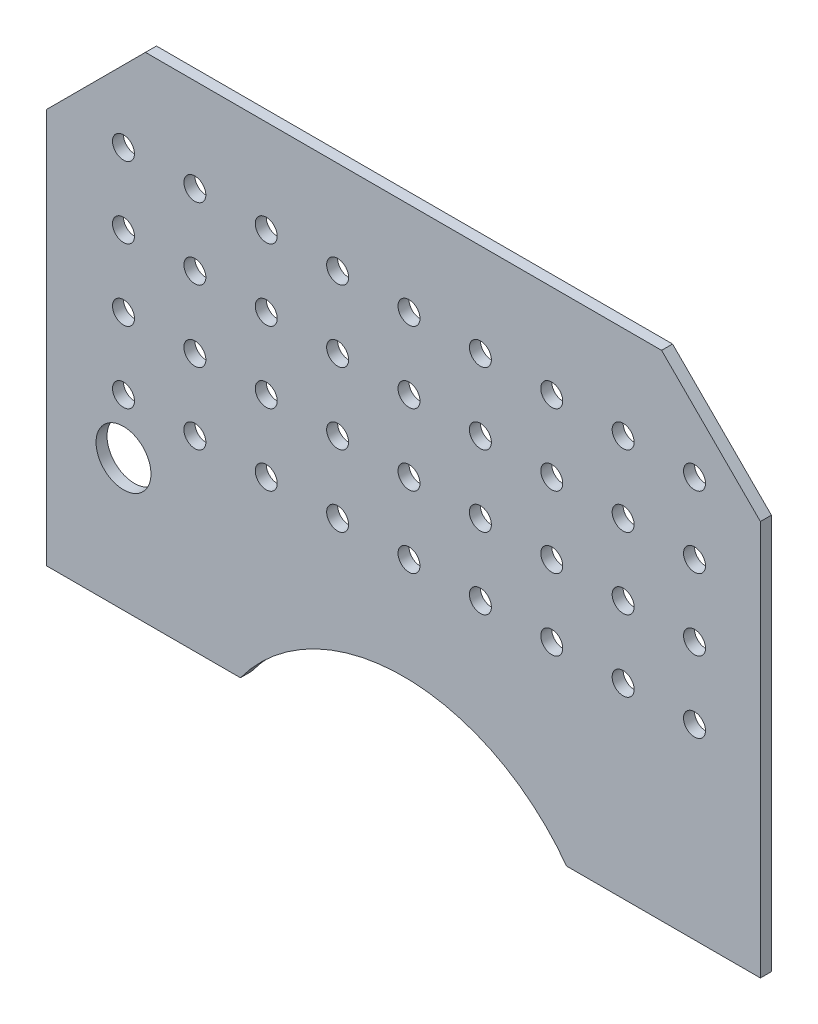
SolidWorks part; units mm, degrees
ref_plane "Front Plane" through (0, 0, 0) normal (0, 0, 1) x (1, 0, 0)
ref_plane "Top Plane" through (0, 0, 0) normal (0, 1, 0) x (1, 0, 0)
ref_plane "Right Plane" through (0, 0, 0) normal (1, 0, 0) x (0, 0, -1)
sketch "Эскиз1" plane through (0, 0, 0) normal (0, 0, 1) x (1, 0, 0)
  line L0 (3.78, -22.45) -> (2.015, -22.45)
  line L1 (0.76, -22.45) -> (3.78, -22.45) construction
  line L2 (2.015, -22.45) -> (2.015, -18.85)
  line L3 (2.015, -18.85) -> (2.915, -17.95)
  line L4 (2.915, -17.95) -> (7.615, -17.95)
  line L5 (5.265, -17.95) -> (5.265, -21.6965) construction
  line L6 (8.515, -18.85) -> (7.615, -17.95)
  line L7 (8.515, -22.45) -> (8.515, -18.85)
  line L8 (6.75, -22.45) -> (8.515, -22.45)
  arc A0 (6.75, -22.45) -> (3.78, -22.45) centre (5.265, -23.5365) ccw construction
  arc A1 (6.75, -22.45) -> (3.78, -22.45) centre (5.265, -23.5365) ccw
  dimension "D1" = 4.5
  dimension "D2" = 6.5
  dimension "D3" = 45
  dimension "D4" = 4.7
extrude "Бобышка-Вытянуть1" add sketch "Эскиз1" along normal blind 0.1
sketch "Эскиз2" plane through (0, 0, 0.1) normal (0, 0, 1) x (1, 0, 0)
  line L0 (2.015, -22.45) -> (3.78, -22.45) construction
  line L1 (2.015, -18.85) -> (2.015, -22.45) construction
  circle A0 centre (2.715, -21.25) radius 0.25
  dimension "D1" = 0.5
  dimension "D2" = 1.2
  dimension "D3" = 0.7
extrude "Вырез-Вытянуть1" cut sketch "Эскиз2" against normal through all
sketch "Эскиз3" plane through (0, 0, 0.1) normal (0, 0, 1) x (1, 0, 0)
  line L0 (2.015, -18.85) -> (2.015, -22.45) construction
  circle A0 centre (2.715, -20.75) radius 0.1
  circle A1 centre (2.715, -21.25) radius 0.25 construction
  circle A2 centre (3.365, -20.75) radius 0.1
  circle A3 centre (4.015, -20.75) radius 0.1
  circle A4 centre (4.665, -20.75) radius 0.1
  circle A5 centre (5.315, -20.75) radius 0.1
  circle A6 centre (5.965, -20.75) radius 0.1
  circle A7 centre (6.615, -20.75) radius 0.1
  circle A8 centre (7.265, -20.75) radius 0.1
  circle A9 centre (7.915, -20.75) radius 0.1
  circle A10 centre (3.365, -20.1) radius 0.1
  circle A11 centre (4.015, -20.1) radius 0.1
  circle A12 centre (4.665, -20.1) radius 0.1
  circle A13 centre (5.315, -20.1) radius 0.1
  circle A14 centre (5.965, -20.1) radius 0.1
  circle A15 centre (6.615, -20.1) radius 0.1
  circle A16 centre (7.265, -20.1) radius 0.1
  circle A17 centre (7.915, -20.1) radius 0.1
  circle A18 centre (3.365, -19.45) radius 0.1
  circle A19 centre (4.015, -19.45) radius 0.1
  circle A20 centre (4.665, -19.45) radius 0.1
  circle A21 centre (5.315, -19.45) radius 0.1
  circle A22 centre (5.965, -19.45) radius 0.1
  circle A23 centre (6.615, -19.45) radius 0.1
  circle A24 centre (7.265, -19.45) radius 0.1
  circle A25 centre (7.915, -19.45) radius 0.1
  circle A26 centre (3.365, -18.8) radius 0.1
  circle A27 centre (4.015, -18.8) radius 0.1
  circle A28 centre (4.665, -18.8) radius 0.1
  circle A29 centre (5.315, -18.8) radius 0.1
  circle A30 centre (5.965, -18.8) radius 0.1
  circle A31 centre (6.615, -18.8) radius 0.1
  circle A32 centre (7.265, -18.8) radius 0.1
  circle A33 centre (7.915, -18.8) radius 0.1
  circle A34 centre (2.715, -20.1) radius 0.1
  circle A35 centre (2.715, -19.45) radius 0.1
  circle A36 centre (2.715, -18.8) radius 0.1
  dimension "D1" = 0.2
  dimension "D2" = 0.5
  dimension "D3" = 0.7
  dimension "D4" = 9
  dimension "D5" = 4
extrude "Вырез-Вытянуть2" cut sketch "Эскиз3" against normal through all
